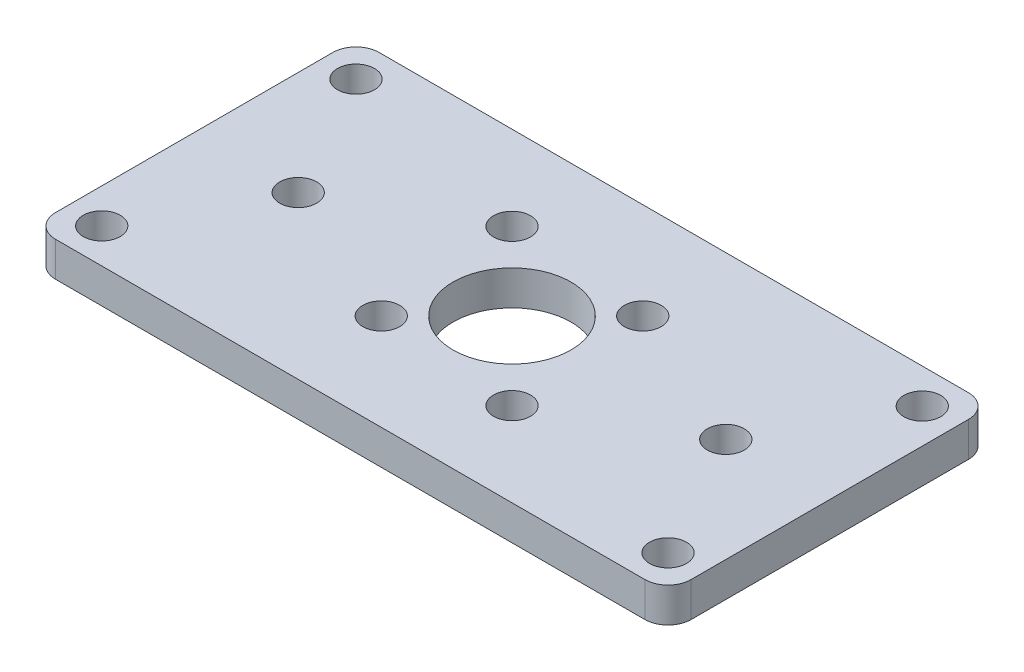
SolidWorks part; units mm, degrees
material "Thornel Mat VMA"
ref_plane "前视基准面" through (0, 0, 0) normal (0, 0, 1) x (1, 0, 0)
ref_plane "上视基准面" through (0, 0, 0) normal (0, 1, 0) x (1, 0, 0)
ref_plane "右视基准面" through (0, 0, 0) normal (1, 0, 0) x (0, 0, -1)
other "Configuration Table"
sketch "草图1" plane through (0, 0, 0) normal (0, 1, 0) x (1, 0, 0)
  line L0 (0, 0) -> (5.6569, 5.6569) construction
  line L1 (-27.5, -14) -> (27.5, -14)
  line L2 (-27.5, -14) -> (-27.5, 14)
  line L3 (-27.5, 14) -> (27.5, 14)
  line L4 (27.5, -14) -> (27.5, 14)
  line L5 (-27.5, -14) -> (27.5, 14) construction
  line L6 (-27.5, 14) -> (27.5, -14) construction
  line L7 (0, 0) -> (27.5, 0) construction
  line L8 (6.7175, -6.7175) -> (0, 0) construction
  circle A0 centre (0, 0) radius 5.1
  circle A1 centre (0, 0) radius 8 construction
  circle A6 centre (0, 0) radius 9.5 construction
  circle A11 centre (5.6569, 5.6569) radius 1.6
  circle A13 centre (5.6569, -5.6569) radius 1.6 construction
  circle A14 centre (-5.6569, -5.6569) radius 1.6
  circle A15 centre (-5.6569, 5.6569) radius 1.6 construction
  circle A16 centre (6.7175, -6.7175) radius 1.6
  circle A17 centre (-6.7175, -6.7175) radius 1.6 construction
  circle A18 centre (-6.7175, 6.7175) radius 1.6
  circle A19 centre (6.7175, 6.7175) radius 1.6 construction
  point P0 (0, 0)
  point P14 (0, 0)
  point P17 (0, 0)
  point P20 (0, 0)
  point P23 (0, 0)
  point P28 (0, 0)
  point P41 (0, 0)
  dimension "D3" = 10.2
  dimension "D4" = 16
  dimension "D5" = 3.2
  dimension "D7" = 19
  dimension "D1" = 28
  dimension "D2" = 55
  dimension "D8" = 45
  dimension "D9" = 4
  dimension "D10" = 90
  dimension "D6" = 4
  dimension "D11" = 4
extrude "凸台-拉伸1" add sketch "草图1" along normal blind 3
sketch "草图2" plane through (0, 3, 0) normal (0, 1, 0) x (1, 0, 0)
  line L0 (27.5, -14) -> (27.5, 14) construction
  line L1 (-27.5, -8) -> (27.5, -8) construction
  line L2 (-27.5, -8) -> (-27.5, 8) construction
  line L3 (-27.5, 8) -> (27.5, 8) construction
  line L4 (27.5, -8) -> (27.5, 8) construction
  line L5 (-27.5, -8) -> (27.5, 8) construction
  line L6 (-27.5, 8) -> (27.5, -8) construction
  line L7 (27.5, 8) -> (27.5, 14) construction
  line L8 (27.5, 14) -> (-27.5, 14) construction
  line L9 (27.5, 11) -> (-27.5, 11) construction
  line L10 (-27.5, 14) -> (-27.5, -14) construction
  line L11 (0, 14) -> (0, -14) construction
  line L12 (-27.5, -14) -> (27.5, -14) construction
  line L13 (-27.5, 0) -> (27.5, 0) construction
  circle A4 centre (-24.5, 11) radius 1.6
  circle A5 centre (-24.5, -11) radius 1.6
  circle A6 centre (24.5, 11) radius 1.6
  circle A7 centre (24.5, -11) radius 1.6
  circle A8 centre (422.7031, 0) radius 1.6 construction
  circle A9 centre (422.7031, 0) radius 1.6
  circle A10 centre (18.5, 0) radius 1.6
  circle A11 centre (-18.5, 0) radius 1.6
  point P0 (0, 0)
  dimension "D2" = 3.2
  dimension "D4" = 3.2
  dimension "D7" = 3
  dimension "D1" = 16
  dimension "D5" = 3
  dimension "D6" = 3
  dimension "D8" = 3
extrude "切除-拉伸1" cut sketch "草图2" against normal through all
fillet "圆角1" radius 2 4 edges at (27.5, 1.5, 14) (-27.5, 1.5, 14) (27.5, 1.5, -14) (-27.5, 1.5, -14)
